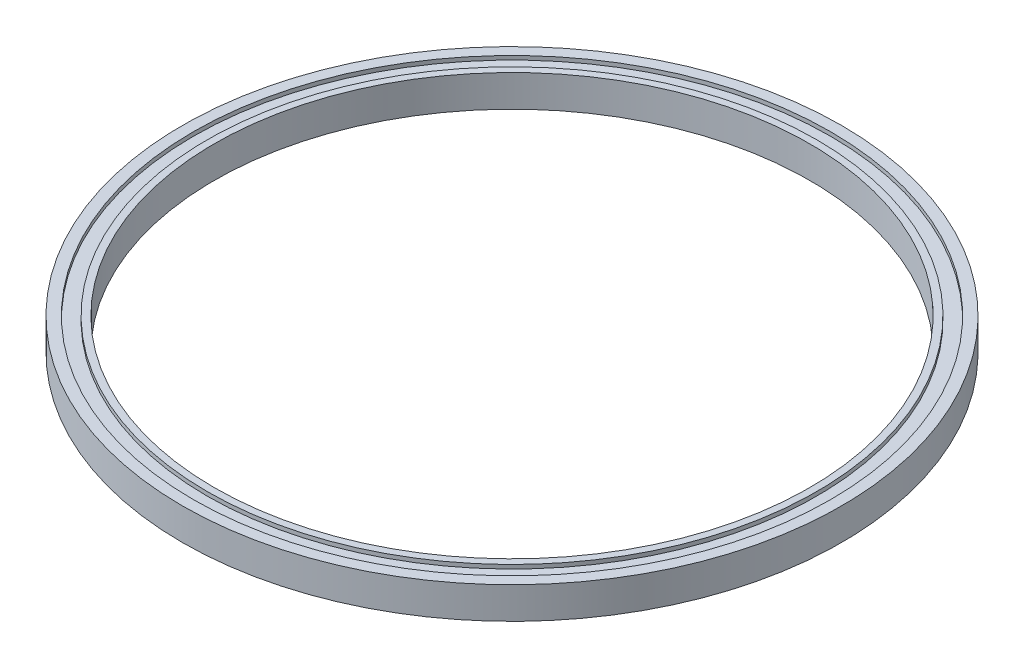
SolidWorks part; units mm, degrees
ref_plane "前视基准面" through (0, 0, 0) normal (0, 0, 1) x (1, 0, 0)
ref_plane "上视基准面" through (0, 0, 0) normal (0, 1, 0) x (1, 0, 0)
ref_plane "右视基准面" through (0, 0, 0) normal (1, 0, 0) x (0, 0, -1)
sketch "草图1" plane through (0, 0, 0) normal (0, 0, 1) x (1, 0, 0)
  line L0 (0, 122.6223) -> (0, -120.2245) construction
  line L1 (-138.3633, 0) -> (167.2601, 0) construction
  line L2 (75, 4) -> (76.75, 4)
  line L3 (76.75, 4) -> (76.75, 3)
  line L4 (76.75, 3) -> (80.25, 3)
  line L5 (80.25, 3) -> (80.25, 4)
  line L6 (80.25, 4) -> (83, 4)
  line L7 (83, 4) -> (83, -4)
  line L8 (75, 4) -> (75, -4)
  line L9 (80.25, -4) -> (83, -4)
  line L10 (80.25, -3) -> (80.25, -4)
  line L11 (76.75, -3) -> (80.25, -3)
  line L12 (76.75, -4) -> (76.75, -3)
  line L13 (75, -4) -> (76.75, -4)
  point P14 (83, 0)
  point P19 (75, 0)
  dimension "D1" = 150
  dimension "D2" = 166
  dimension "D3" = 8
  dimension "D4" = 153.5
  dimension "D5" = 160.5
  dimension "D6" = 1
revolve "旋转1" add sketch "草图1" angle 360 about L0
move or copy body "实体-移动/复制1" [suppressed] bodies to move or copy 106
